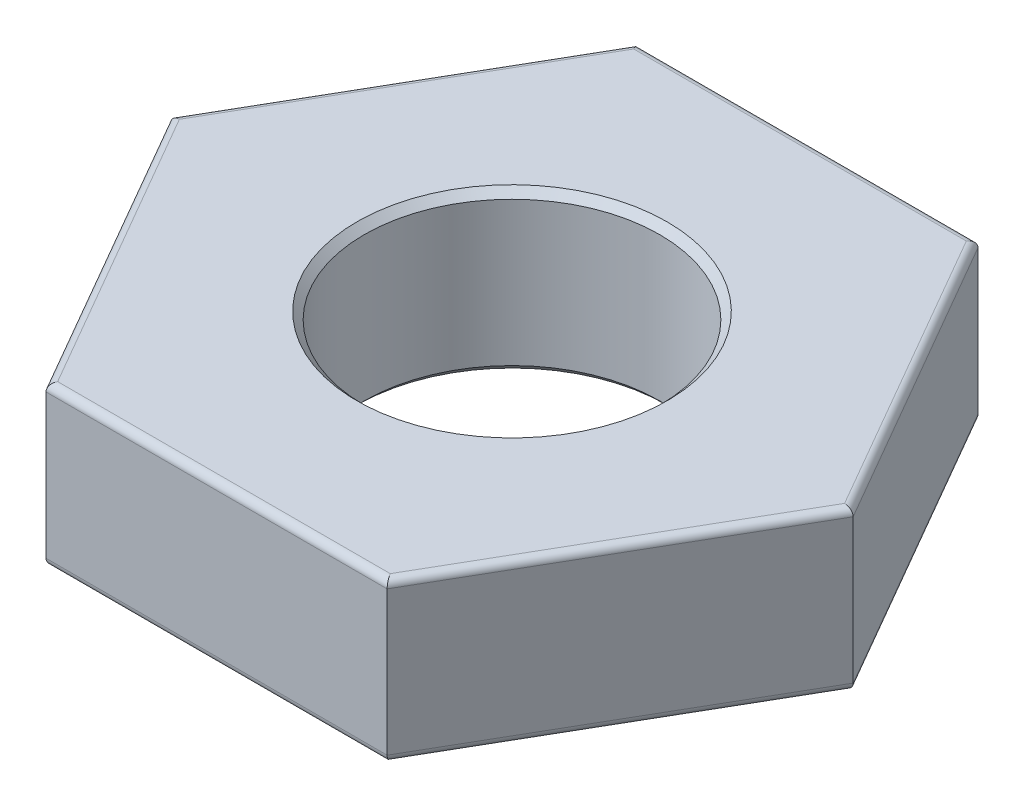
SolidWorks part; units mm, degrees
ref_plane "Front Plane" through (0, 0, 0) normal (0, 0, 1) x (1, 0, 0)
ref_plane "Top Plane" through (0, 0, 0) normal (0, 1, 0) x (1, 0, 0)
ref_plane "Right Plane" through (0, 0, 0) normal (1, 0, 0) x (0, 0, -1)
sketch "Sketch1" plane through (0, 0, 0) normal (0, 1, 0) x (1, 0, 0)
  line L0 (-2.3094, 4) -> (2.3094, 4)
  line L1 (2.3094, 4) -> (4.6188, 0)
  line L2 (4.6188, 0) -> (2.3094, -4)
  line L3 (2.3094, -4) -> (-2.3094, -4)
  line L4 (-2.3094, -4) -> (-4.6188, 0)
  line L5 (-4.6188, 0) -> (-2.3094, 4)
  circle A0 centre (0, 0) radius 2
  circle A1 centre (0, 0) radius 4
  point P6 (-4.0391, 5.5848)
  point P11 (-3.3761, 5.8555)
  dimension "D1" = 4
  dimension "D2" = 8
extrude "Boss-Extrude1" add sketch "Sketch1" along normal blind 2.15 contours A0 | L0 L1 L2 L3 L4 L5
fillet "Fillet1" radius 0.1 12 edges at (0, 0, 4) (-3.4641, 0, 2) (-3.4641, 0, -2) (0, 0, -4) (3.4641, 0, -2) (3.4641, 0, 2) (3.4641, 2.15, 2) (3.4641, 2.15, -2) (0, 2.15, -4) (-3.4641, 2.15, -2) (-3.4641, 2.15, 2) (0, 2.15, 4)
chamfer "Chamfer1" distance 0.1 angle 45 2 edges at (0, 2.15, 2) (0, 0, 2)
